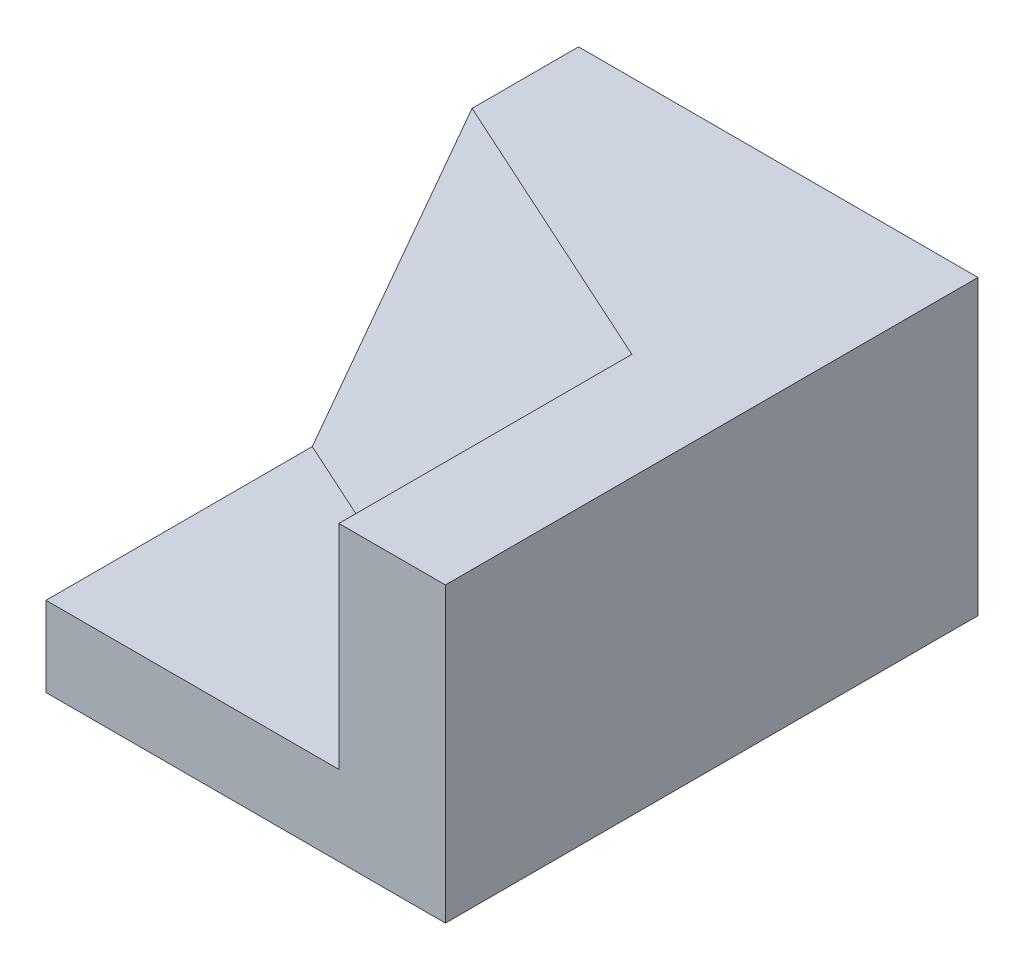
SolidWorks part; units mm, degrees
ref_plane "Front Plane" through (0, 0, 0) normal (0, 0, 1) x (1, 0, 0)
ref_plane "Top Plane" through (0, 0, 0) normal (0, 1, 0) x (1, 0, 0)
ref_plane "Right Plane" through (0, 0, 0) normal (1, 0, 0) x (0, 0, -1)
sketch "Sketch2" plane through (0, 0, 0) normal (0, 0, 1) x (1, 0, 0)
  line L0 (0, 0) -> (-75, 0)
  line L1 (-75, 0) -> (-75, 15)
  line L2 (-75, 15) -> (-20, 15)
  line L3 (-20, 15) -> (-20, 55)
  line L4 (-20, 55) -> (0, 55)
  line L5 (0, 55) -> (0, 0)
  dimension "D1" = 75
  dimension "D2" = 20
  dimension "D3" = 15
  dimension "D4" = 55
extrude "Boss-Extrude1" add sketch "Sketch2" along normal blind 100
sketch "Sketch3" plane through (0, 0, 100) normal (0, 0, 1) x (1, 0, 0)
  line L1 (-20, 15) -> (-75, 15)
  line L2 (-20, 15) -> (-20, 55)
  line L3 (-20, 55) -> (-75, 55)
  line L4 (-75, 15) -> (-75, 55)
  dimension "D1" = 55
  dimension "D2" = 40
extrude "Boss-Extrude2" add sketch "Sketch3" against normal blind 75 from offset 25 offset against normal yes
sketch "Sketch4" plane through (0, 55, 0) normal (0, 1, 0) x (1, 0, 0)
  line L0 (-75, 0) -> (-75, -75) construction
  line L2 (-20, -100) -> (-20, -75) construction
  line L3 (0, 0) -> (-75, 0) construction
  point P0 (-20, -45)
  point P1 (-75, -20)
  dimension "D1" = 45
  dimension "D2" = 20
sketch "Sketch5" plane through (-75, 0, 0) normal (-1, 0, 0) x (0, 0, 1)
  line L0 (100, 15) -> (75, 15) construction
  line L1 (0, -30.25) -> (0, 30.25) construction
  point P0 (50, 15)
  dimension "D1" = 50
ref_plane "Plane1" through (-24.4964, 40.419, 53.892) normal (-0.3417, 0.5639, 0.7518) x (0.9398, 0.205, 0.2734)
sketch "Sketch6" plane through (-24.4964, 40.419, 53.892) normal (-0.3417, 0.5639, 0.7518) x (0.9398, 0.205, 0.2734)
  line L0 (4.7844, 17) -> (-53.7391, 32)
  line L1 (-53.7391, 32) -> (-53.7391, -18)
  line L2 (-53.7391, -18) -> (4.7844, -33)
  line L3 (4.7844, -33) -> (4.7844, 17)
extrude "Cut-Extrude1" cut sketch "Sketch6" along direction (0, 0, -1) on the side of the normal blind 75 contours L0 L1 L2 L3
